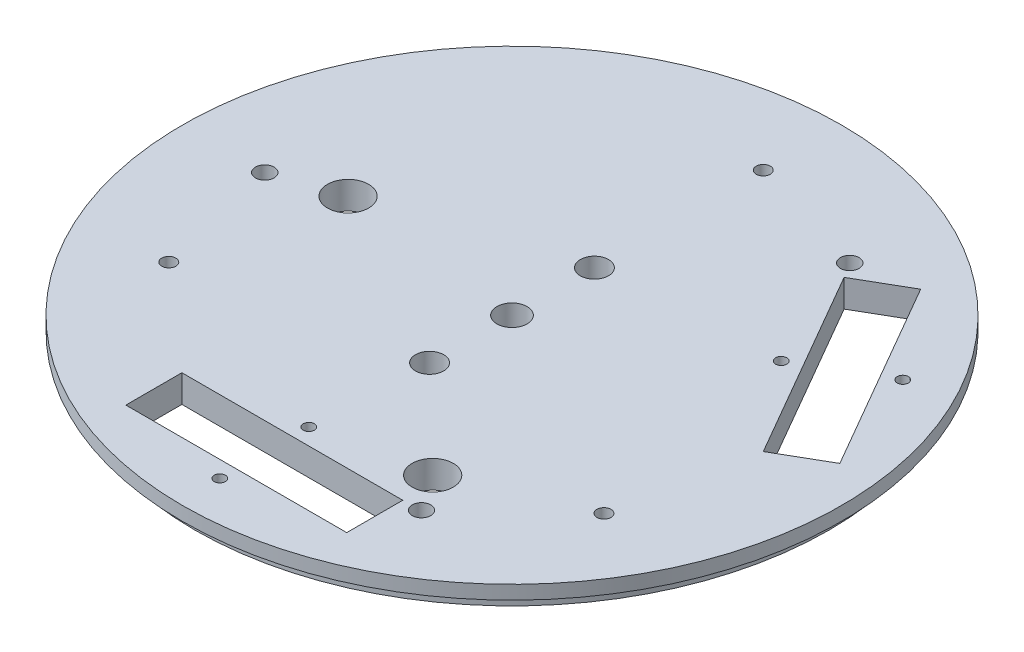
SolidWorks part; units mm, degrees
ref_plane "Front Plane" through (0, 0, 0) normal (0, 0, 1) x (1, 0, 0)
ref_plane "Top Plane" through (0, 0, 0) normal (0, 1, 0) x (1, 0, 0)
ref_plane "Right Plane" through (0, 0, 0) normal (1, 0, 0) x (0, 0, -1)
sketch "Sketch1" plane through (0, 0, 0) normal (0, 1, 0) x (1, 0, 0)
  circle A0 centre (0, 0) radius 76.1746
  dimension "D1" = 152.3492
extrude "Boss-Extrude1" add sketch "Sketch1" against normal blind 3.175
sketch "Sketch3" plane through (0, -3.175, 0) normal (0, -1, 0) x (1, 0, 0)
  circle A0 centre (0, 0) radius 73.3171
  dimension "D1" = 146.6342
extrude "Boss-Extrude2" add sketch "Sketch3" along normal blind 3.175
hole_wizard "#97 (0.0059) Diameter Hole1" positions "Sketch4" profile "Sketch5" hole size "#97" standard "ANSI Inch"
sketch "Sketch4" plane through (0, -6.35, 0) normal (0, -1, 0) x (-1, 0, 0)
  point P0 (0, 0)
  point P3 (0, 0)
sketch "Sketch5" plane through (0, -6.35, 0) normal (1, 0, 0) x (0, 0, -1)
  line L0 (0, 0) -> (0, 12.024)
  line L1 (0, 12.024) -> (3.4925, 10.0076)
  line L2 (3.4925, 10.0076) -> (3.4925, 0)
  line L5 (3.4925, 0) -> (0, 0)
  line L10 (0, 12.024) -> (-3.4925, 10.0076) construction
  line L11 (0, -6.35) -> (0, 107.95) construction
  dimension "Hole Dia." = 6.985
  dimension "Hole Depth" = 10.0076
  dimension "Drill Angle" = 120
hole_wizard "#97 (0.0059) Diameter Hole3" positions "Sketch7" profile "Sketch8" hole size "#97" standard "ANSI Inch"
sketch "Sketch7" plane through (0, 0, 0) normal (0, 1, 0) x (1, 0, 0)
  line L0 (0, 38.1) -> (0, 0) construction
  point P7 (0, 19.05)
  dimension "D1" = 19.05
sketch "Sketch8" plane through (0, 0, -19.05) normal (1, 0, 0) x (0, 0, 1)
  line L0 (0, 0) -> (0, 11.892)
  line L1 (0, 11.892) -> (3.2639, 10.0076)
  line L2 (3.2639, 10.0076) -> (3.2639, 0)
  line L5 (3.2639, 0) -> (0, 0)
  line L10 (0, 11.892) -> (-3.2639, 10.0076) construction
  line L11 (0, -6.35) -> (0, 107.95) construction
  dimension "Hole Dia." = 6.5278
  dimension "Hole Depth" = 10.0076
  dimension "Drill Angle" = 120
mirror "Mirror1" about plane through (0, 0, 0) normal (0, 0, 1) of "#97 (0.0059) Diameter Hole3"
sketch "Sketch9" plane through (0, 0, 0) normal (0, 1, 0) x (1, 0, 0)
  line L0 (-26.6446, -49.657) -> (24.4094, -49.657)
  line L1 (-26.6446, -49.657) -> (-26.6446, -62.611)
  line L2 (24.4094, -49.657) -> (24.4094, -62.611)
  line L3 (-26.6446, -62.611) -> (24.4094, -62.611)
  line L4 (0, -3.4925) -> (0, 3.4925) construction
  line L5 (-1.1176, -62.611) -> (-1.1176, -66.421) construction
  line L6 (-26.6446, -56.134) -> (24.4094, -56.134) construction
  line L10 (0, 0) -> (0, -104.3762) construction
  circle A0 centre (-1.1176, -66.421) radius 1.292
  circle A1 centre (-1.1176, -45.847) radius 1.292
  point P15 (-1.1176, -49.657)
  dimension "D1" = 0
  dimension "D2" = 51.054
  dimension "D3" = 12.954
  dimension "D4" = 3.81
  dimension "D5" = 1.1176
  dimension "D6" = 56.134
extrude "Cut-Extrude1" cut sketch "Sketch9" against normal through all
sketch "Sketch10" plane through (0, 0, 0) normal (0, 1, 0) x (1, 0, 0)
  circle A0 centre (41.148, 24.1554) radius 4.7625
  dimension "D1" = 9.525
  dimension "D2" = 41.148
  dimension "D3" = 24.1554
sketch "Sketch11" plane through (0, 0, 0) normal (0, 1, 0) x (1, 0, 0)
  line L0 (0, 0) -> (50000, 0) construction
  line L1 (-0.0402, -0.0696) -> (49.6594, 86.0127) construction
  circle A0 centre (28.575, 49.4934) radius 2.159
  dimension "D2" = 4.318
  dimension "D1" = 60
  dimension "D3" = 57.15
extrude "Cut-Extrude3" cut sketch "Sketch11" against normal through all both and the other way through all
sketch "Sketch14" plane through (0, 0, 0) normal (0, 0, 1) x (1, 0, 0)
  line L0 (0, 0) -> (0, 9.7326) construction
pattern_circular "CirPattern2" count 3 every 120 about axis through (0, 0, 0) along (0, 1, 0) of "Cut-Extrude3"
sketch "Sketch15" plane through (0, 0, 0) normal (0, 1, 0) x (1, 0, 0)
  circle A0 centre (-42.78, 4.89) radius 4.7625
  circle A1 centre (22.86, -41.19) radius 4.7625
  dimension "D1" = 9.525
  dimension "D4" = 9.525
  dimension "D5" = 41.19
  dimension "D2" = 42.78
  dimension "D3" = 4.89
  dimension "D6" = 22.86
extrude "Cut-Extrude4" cut sketch "Sketch15" against normal up to surface (6.35 mm away) up to face at (26.7053, -6.35, 48.4139)
hole_wizard "Hole1" positions "Sketch18" profile "Sketch17" hole size "#4" standard "ANSI Inch" end condition through all
sketch "Sketch18" plane through (0, 0, 0) normal (0, 1, 0) x (1, 0, 0)
  line L0 (0, -3.4925) -> (0, 3.4925) construction
  point P0 (0, 58.0746)
  dimension "D1" = 58.0746
sketch "Sketch17" plane through (0, 0, -58.0746) normal (1, 0, 0) x (0, 0, 1)
  line L0 (0, 0) -> (0, 6.35)
  line L1 (0, 6.35) -> (1.6319, 6.35)
  line L2 (1.6319, 6.35) -> (1.6319, 0)
  line L5 (1.6319, 0) -> (0, 0)
  line L11 (0, -6.35) -> (0, 107.95) construction
  dimension "Thru Hole Dia." = 3.2639
  dimension "Thru Hole Depth" = 6.35
pattern_circular "CirPattern3" count 3 over 240 about axis through (0, 0, 0) along (0, 1, 0) of "Hole1"
pattern_circular "CirPattern4" count 2 every 120 about axis through (0, 0, 0) along (0, 1, 0) of "Cut-Extrude1"
